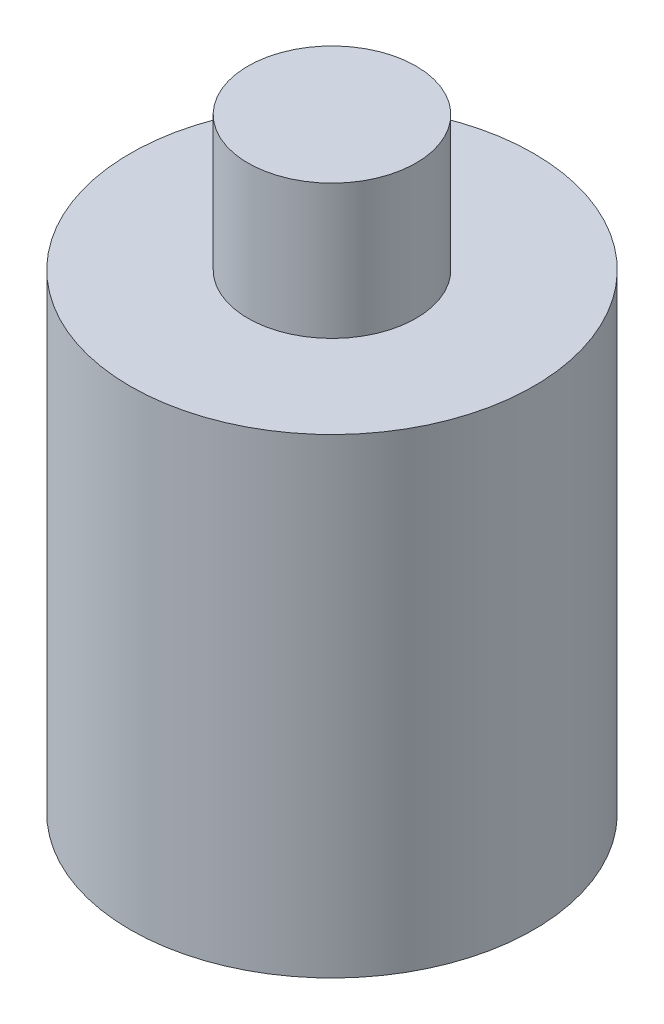
SolidWorks part; units mm, degrees
ref_plane "Plano frontal" through (0, 0, 0) normal (0, 0, 1) x (1, 0, 0)
ref_plane "Plano superior" through (0, 0, 0) normal (0, 1, 0) x (1, 0, 0)
ref_plane "Plano direito" through (0, 0, 0) normal (1, 0, 0) x (0, 0, -1)
sketch "Esboço1" plane through (0, 0, 0) normal (0, 0, 1) x (1, 0, 0)
  line L0 (0, 0) -> (0, 9.8989) construction
  line L1 (0, 0) -> (5.5054, 0) construction
  line L2 (0, 9) -> (0, 2.7)
  line L5 (1.25, 7) -> (3, 7)
  line L6 (3, 0) -> (3, 7)
  line L9 (0, 9) -> (1.25, 9)
  line L10 (1.25, 7) -> (1.25, 9)
  line L14 (1.6, 0) -> (3, 0)
  line L15 (1.6, 0) -> (1.6, 2.7)
  line L16 (1.6, 2.7) -> (0, 2.7)
  dimension "D1" = 1.25
  dimension "D2" = 9
  dimension "D3" = 3
  dimension "D4" = 2
  dimension "D5" = 2.7
  dimension "D6" = 1.6
revolve "Revolução1" add sketch "Esboço1" angle 360 about L0
